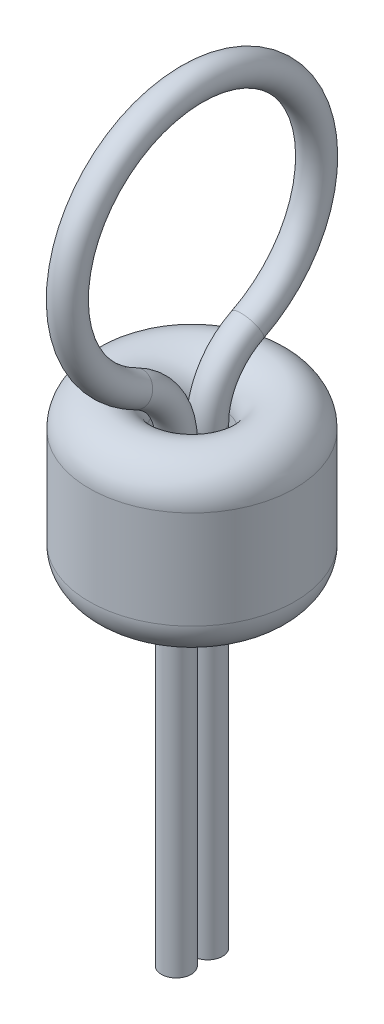
SolidWorks part; units mm, degrees
ref_plane "Front Plane" through (0, 0, 0) normal (0, 0, 1) x (1, 0, 0)
ref_plane "Top Plane" through (0, 0, 0) normal (0, 1, 0) x (1, 0, 0)
ref_plane "Right Plane" through (0, 0, 0) normal (1, 0, 0) x (0, 0, -1)
sketch "Sketch1" plane through (0, 0, 0) normal (1, 0, 0) x (0, 0, -1)
  line L0 (0, 7.345) -> (0, -6.6898) construction
  line L1 (-0.36, 2.9019) -> (-0.36, -2.9019)
  line L2 (0.36, 2.9019) -> (0.36, -2.9019)
  line L3 (0, 6.8981) -> (-6.3968, 6.8981) construction
  line L4 (-0.36, -2.9019) -> (-6.927, -2.9019) construction
  line L5 (-0.36, -2.9019) -> (-0.2, -2.9019) construction
  line L6 (-0.36, 3.3981) -> (-0.36, 2.9019) construction
  line L7 (0.36, 3.3981) -> (0.36, 2.9019) construction
  arc A0 (-0.7809, 3.582) -> (0.7809, 3.582) centre (0, 5.1481) cw
  arc A1 (-0.3961, 3.4435) -> (-0.36, 3.3981) centre (-0.4066, 3.3981) cw construction
  arc A2 (0.3961, 3.4435) -> (0.36, 3.3981) centre (0.4066, 3.3981) ccw construction
  arc A3 (-0.36, 2.9019) -> (-0.7809, 3.582) centre (-1.12, 2.9019) ccw
  arc A4 (-0.3961, 3.4435) -> (-0.7809, 3.582) centre (0, 5.1481) cw construction
  arc A5 (0.36, 2.9019) -> (0.7809, 3.582) centre (1.12, 2.9019) cw
  arc A6 (0.7809, 3.582) -> (0.3961, 3.4435) centre (0, 5.1481) cw construction
  point P8 (-0.36, 0)
  point P11 (-0.35, 2.5926)
  dimension "D1" = 1.75
  dimension "D6" = 0.76
  dimension "D2" = 9.8
  dimension "D3" = 6.3
  dimension "D4" = 0.16
  dimension "D5" = 0.4
sketch "Sketch2" plane through (0, 0, 0) normal (0, 1, 0) x (1, 0, 0)
  circle A0 centre (0, -0.2) radius 0.19
  point P2 (0, 0)
  dimension "D1" = 0.38
sweep "Sweep3" add profiles "Sketch2" path "Sketch1"
sketch "Sketch8" plane through (0, 0, 0) normal (1, 0, 0) x (0, 0, -1)
  line L0 (-0.86, 2.925) -> (-0.86, 1.675) construction
  line L1 (-0.41, 2.925) -> (-0.41, 1.675)
  line L2 (-1.31, 2.925) -> (-1.31, 1.675)
  line L3 (-0.86, 3.375) -> (-3.2483, 3.375) construction
  line L4 (-0.86, 1.225) -> (-3.2483, 1.225) construction
  line L5 (0, 0) -> (0, 5.0192) construction
  arc A0 (-0.41, 2.925) -> (-1.31, 2.925) centre (-0.86, 2.925) ccw
  arc A1 (-1.31, 1.675) -> (-0.41, 1.675) centre (-0.86, 1.675) ccw
  point P2 (-0.86, 2.3)
  dimension "D1" = 2.15
  dimension "D2" = 0.9
  dimension "D3" = 2.3
  dimension "D4" = 0.86
revolve "Revolve1" add sketch "Sketch8" angle 360 about L5
